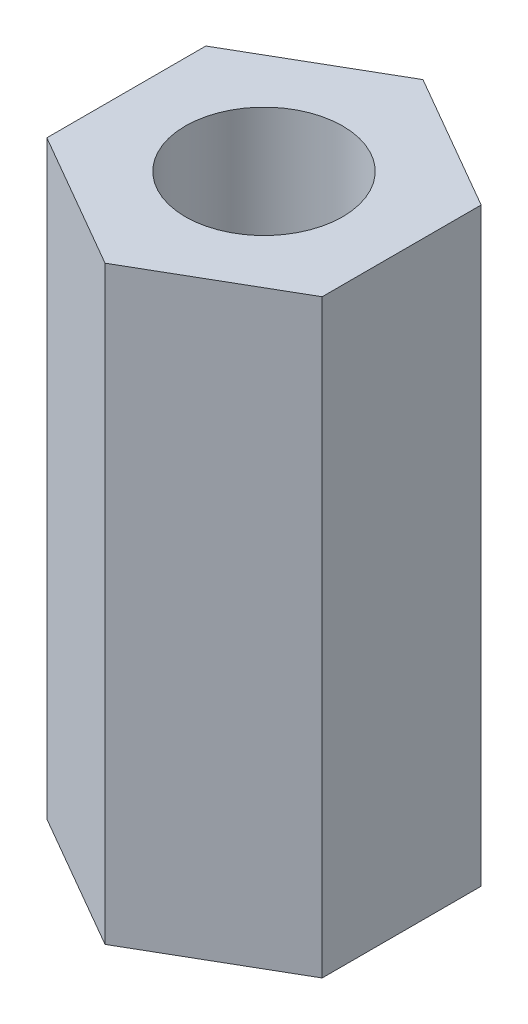
SolidWorks part; units mm, degrees
ref_plane "Front Plane" through (0, 0, 0) normal (0, 0, 1) x (1, 0, 0)
ref_plane "Top Plane" through (0, 0, 0) normal (0, 1, 0) x (1, 0, 0)
ref_plane "Right Plane" through (0, 0, 0) normal (1, 0, 0) x (0, 0, -1)
sketch "Sketch1" plane through (0, 0, 0) normal (0, 1, 0) x (1, 0, 0)
  line L1 (3.5, 2.0207) -> (0, 4.0415)
  line L2 (0, 4.0415) -> (-3.5, 2.0207)
  line L3 (-3.5, 2.0207) -> (-3.5, -2.0207)
  line L4 (-3.5, -2.0207) -> (0, -4.0415)
  line L5 (0, -4.0415) -> (3.5, -2.0207)
  line L6 (3.5, -2.0207) -> (3.5, 2.0207)
  circle A0 centre (0, 0) radius 3.5 construction
  circle A1 centre (0, 0) radius 2
  dimension "D1" = 7
  dimension "D2" = 4
extrude "Boss-Extrude1" add sketch "Sketch1" along normal blind 15
